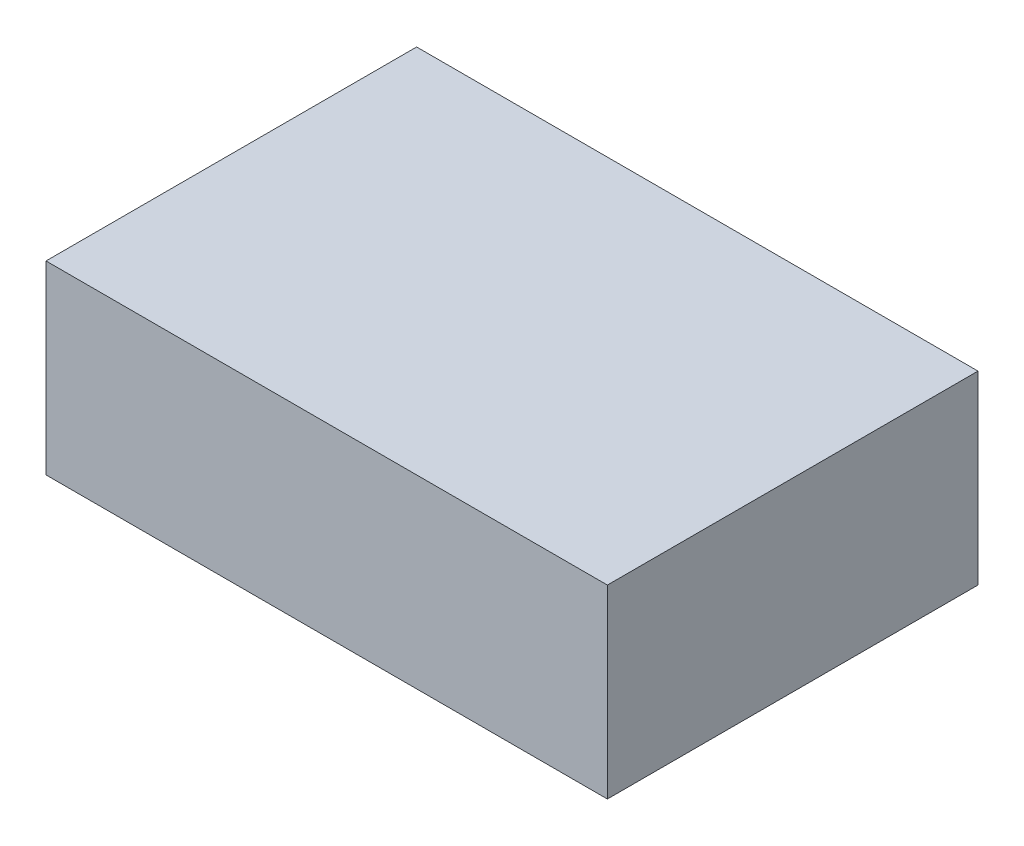
SolidWorks part; units mm, degrees
ref_plane "Front Plane" through (0, 0, 0) normal (0, 0, 1) x (1, 0, 0)
ref_plane "Top Plane" through (0, 0, 0) normal (0, 1, 0) x (1, 0, 0)
ref_plane "Right Plane" through (0, 0, 0) normal (1, 0, 0) x (0, 0, -1)
sketch "Sketch1" plane through (0, 0, 0) normal (0, 1, 0) x (1, 0, 0)
  line L1 (0, 0) -> (261.62, 0)
  line L2 (0, 0) -> (0, 172.72)
  line L3 (0, 172.72) -> (261.62, 172.72)
  line L4 (261.62, 0) -> (261.62, 172.72)
  dimension "D1" = 261.62
  dimension "D2" = 172.72
extrude "Boss-Extrude1" add sketch "Sketch1" along normal blind 86.36 contours L1 L4 L3 L2
equation "\"length\"= 10.3"
equation "\"D1@Sketch1\"=\"length\""
equation "\"width\"= 6.8"
equation "\"D2@Sketch1\"=\"width\""
equation "\"height\"= 3.4"
equation "\"D1@Boss-Extrude1\"=\"height\""
